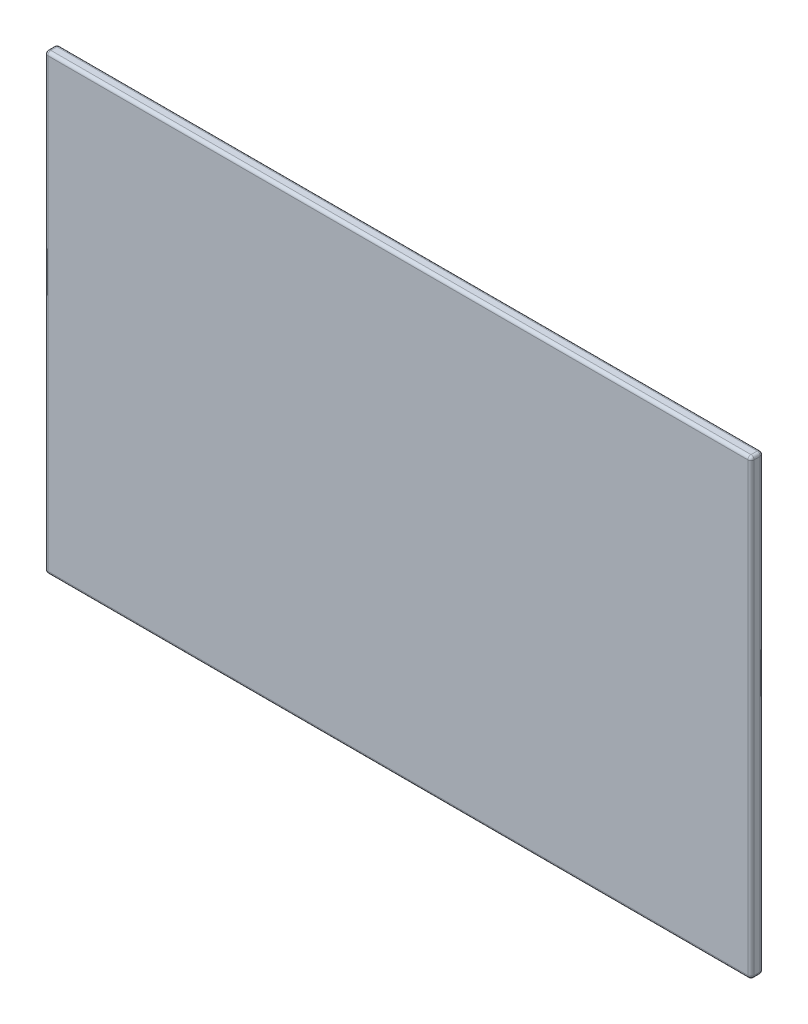
SolidWorks part; units mm, degrees
ref_plane "Front Plane" through (0, 0, 0) normal (0, 0, 1) x (1, 0, 0)
ref_plane "Top Plane" through (0, 0, 0) normal (0, 1, 0) x (1, 0, 0)
ref_plane "Right Plane" through (0, 0, 0) normal (1, 0, 0) x (0, 0, -1)
sketch "Sketch1" plane through (0, 0, 0) normal (0, 0, 1) x (1, 0, 0)
  line L1 (-57.35, -36.75) -> (57.35, -36.75)
  line L2 (-57.35, -36.75) -> (-57.35, 36.75)
  line L3 (-57.35, 36.75) -> (57.35, 36.75)
  line L4 (57.35, -36.75) -> (57.35, 36.75)
  line L5 (-57.35, -36.75) -> (57.35, 36.75) construction
  line L6 (-57.35, 36.75) -> (57.35, -36.75) construction
  point P0 (0, 0)
  dimension "D1" = 114.7
  dimension "D2" = 73.5
extrude "Boss-Extrude1" add sketch "Sketch1" along normal blind 2
fillet "Fillet1" radius 0.5 12 edges at (0, -36.75, 2) (0, -36.75, 0) (-57.35, 0, 2) (-57.35, -36.75, 1) (-57.35, 0, 0) (0, 36.75, 2) (-57.35, 36.75, 1) (0, 36.75, 0) (57.35, -36.75, 1) (57.35, 0, 2) (57.35, 36.75, 1) (57.35, 0, 0)
